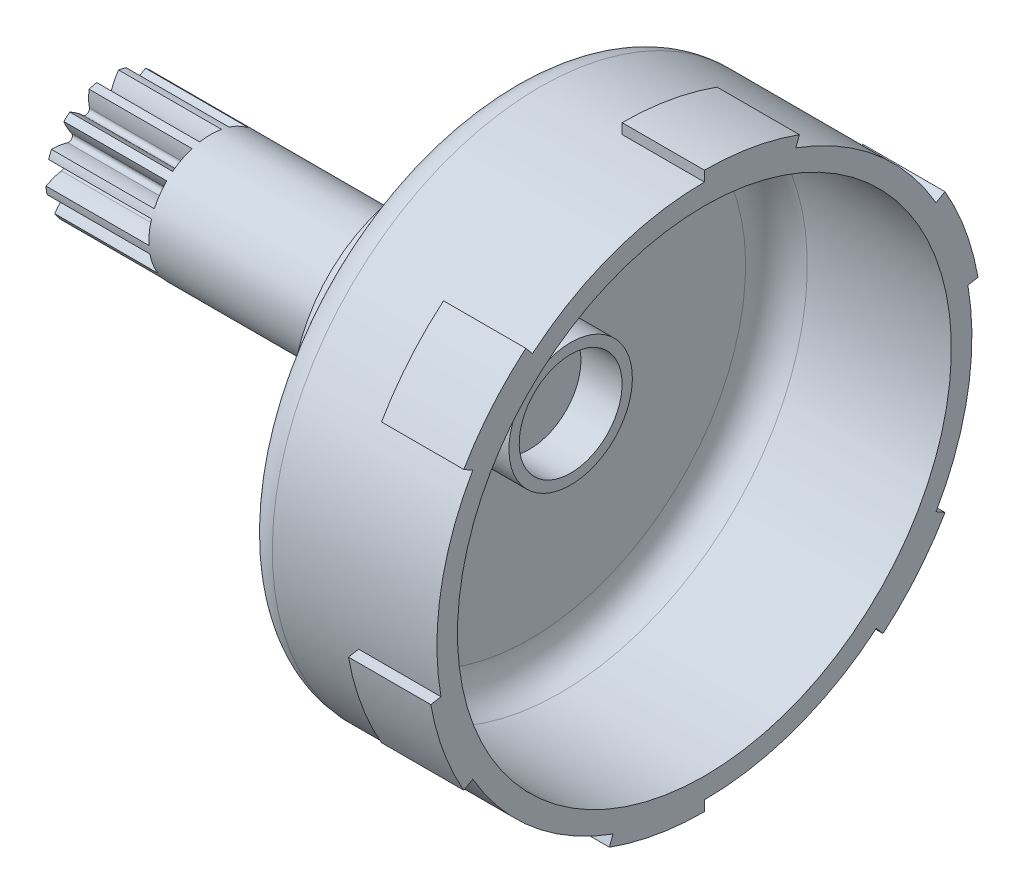
SolidWorks part; units mm, degrees
ref_plane "Front Plane" through (0, 0, 0) normal (0, 0, 1) x (1, 0, 0)
ref_plane "Top Plane" through (0, 0, 0) normal (0, 1, 0) x (1, 0, 0)
ref_plane "Right Plane" through (0, 0, 0) normal (1, 0, 0) x (0, 0, -1)
sketch "Sketch1" plane through (0, 0, 0) normal (0, 0, 1) x (1, 0, 0)
  line L0 (-19, 0) -> (-17, 0)
  line L1 (0, 0) -> (-19, 0) construction
  line L2 (0, 24) -> (0, 26)
  line L3 (0, 26) -> (-16, 26)
  line L4 (-19, 0) -> (-19, 23)
  line L7 (0, 24) -> (-14, 24)
  line L8 (-17, 0) -> (-17, 21)
  arc A0 (-14, 24) -> (-17, 21) centre (-14, 21) ccw
  arc A1 (-16, 26) -> (-19, 23) centre (-16, 23) ccw
  point P12 (-19, 26)
  dimension "D6" = 3
  dimension "D1" = 26
  dimension "D2" = 24
  dimension "D3" = 2
  dimension "D4" = 19
  dimension "D5" = 19
revolve "Revolve1" add sketch "Sketch1" angle 360 about L1
sketch "Sketch2" plane through (-17, 0, 0) normal (1, 0, 0) x (0, 0, -1)
  circle A0 centre (0, 0) radius 6
  circle A1 centre (0, 0) radius 5
  dimension "D1" = 12
  dimension "D2" = 10
extrude "Boss-Extrude1" add sketch "Sketch2" along normal blind 4
sketch "Sketch3" plane through (-19, 0, 0) normal (-1, 0, 0) x (0, 0, 1)
  circle A0 centre (0, 0) radius 12
  dimension "D1" = 24
extrude "Boss-Extrude2" add sketch "Sketch3" along normal blind 9
sketch "Sketch4" plane through (-28, 0, 0) normal (-1, 0, 0) x (0, 0, 1)
  circle A0 centre (0, 0) radius 6
  dimension "D1" = 12
extrude "Boss-Extrude3" add sketch "Sketch4" along normal blind 30
sketch "Sketch5" plane through (0, 0, 0) normal (1, 0, 0) x (0, 0, -1)
  line L0 (0, 26) -> (0, -26) construction
  line L1 (0, 26) -> (0, 27)
  line L2 (8.8925, 24.432) -> (9.2345, 25.3717)
  line L3 (22.5167, 13) -> (23.3827, 13.5)
  line L4 (25.605, 4.5149) -> (26.5898, 4.6885)
  line L5 (22.5167, -13) -> (23.3827, -13.5)
  line L6 (16.7125, -19.9172) -> (17.3553, -20.6832)
  line L7 (0, -26) -> (0, -27)
  line L8 (-8.8925, -24.432) -> (-9.2345, -25.3717)
  line L9 (-22.5167, -13) -> (-23.3827, -13.5)
  line L10 (-25.605, -4.5149) -> (-26.5898, -4.6885)
  line L11 (-22.5167, 13) -> (-23.3827, 13.5)
  line L12 (-16.7125, 19.9172) -> (-17.3553, 20.6832)
  circle A0 centre (0, 0) radius 26 construction
  arc A1 (9.2345, 25.3717) -> (0, 27) centre (0, 0) ccw
  arc A2 (0, 26) -> (8.8925, 24.432) centre (0, 0) cw
  arc A3 (26.5898, 4.6885) -> (23.3827, 13.5) centre (0, 0) ccw
  arc A4 (22.5167, 13) -> (25.605, 4.5149) centre (0, 0) cw
  arc A5 (17.3553, -20.6832) -> (23.3827, -13.5) centre (0, 0) ccw
  arc A6 (22.5167, -13) -> (16.7125, -19.9172) centre (0, 0) cw
  arc A7 (-9.2345, -25.3717) -> (0, -27) centre (0, 0) ccw
  arc A8 (0, -26) -> (-8.8925, -24.432) centre (0, 0) cw
  arc A9 (-26.5898, -4.6885) -> (-23.3827, -13.5) centre (0, 0) ccw
  arc A10 (-22.5167, -13) -> (-25.605, -4.5149) centre (0, 0) cw
  arc A11 (-17.3553, 20.6832) -> (-23.3827, 13.5) centre (0, 0) ccw
  arc A12 (-22.5167, 13) -> (-16.7125, 19.9172) centre (0, 0) cw
  point P34 (0, 0)
  dimension "D1" = 54
  dimension "D2" = 20
  dimension "D3" = 1
  dimension "D5" = 6
extrude "Boss-Extrude4" add sketch "Sketch5" against normal blind 8
sketch "Sketch6" plane through (-58, 0, 0) normal (-1, 0, 0) x (0, 0, 1)
  line L0 (0, 0) -> (0, 6) construction
  arc A0 (-1.06, 5.9056) -> (-0.35, 4.4864) centre (-5.5724, 2.761) cw
  arc A1 (-0.35, 4.4864) -> (0.35, 4.4864) centre (0, 4.602) ccw
  arc A2 (0.35, 4.4864) -> (1.06, 5.9056) centre (5.5724, 2.761) cw
  circle A3 centre (0, 0) radius 6 construction
  circle A4 centre (0, 0) radius 6
  circle A5 centre (0, 0) radius 4.5 construction
  arc A6 (1.8059, 5.7218) -> (1.775, 4.1351) centre (-3.651, 5.0344) cw
  arc A7 (2.3948, 3.8098) -> (3.6831, 4.7366) centre (6.2172, -0.1448) cw
  arc A8 (4.2581, 4.2271) -> (3.4934, 2.8366) centre (-0.8932, 6.1544) cw
  arc A9 (3.891, 2.2605) -> (5.4624, 2.4824) centre (5.4378, -3.0175) cw
  arc A10 (5.7348, 1.7641) -> (4.4115, 0.8882) centre (2.0692, 5.8646) cw
  arc A11 (4.4958, 0.1933) -> (5.9903, -0.3404) centre (3.4126, -5.1989) cw
  arc A12 (5.8977, -1.103) -> (4.3189, -1.2636) centre (4.5576, 4.2312) cw
  arc A13 (4.0707, -1.9181) -> (5.146, -3.0853) centre (0.6056, -6.1893) cw
  arc A14 (4.7096, -3.7175) -> (3.237, -3.126) centre (6.0019, 1.6285) cw
  arc A15 (2.713, -3.5902) -> (3.1227, -5.1233) centre (-2.3401, -5.7618) cw
  arc A16 (2.4425, -5.4803) -> (1.4135, -4.2722) centre (6.0712, -1.3472) cw
  arc A17 (0.7338, -4.4398) -> (0.3841, -5.9877) centre (-4.7497, -4.0144) cw
  arc A18 (-0.3841, -5.9877) -> (-0.7338, -4.4398) centre (4.7497, -4.0144) cw
  arc A19 (-1.4135, -4.2722) -> (-2.4425, -5.4803) centre (-6.0712, -1.3472) cw
  arc A20 (-3.1227, -5.1233) -> (-2.713, -3.5902) centre (2.3401, -5.7618) cw
  arc A21 (-3.237, -3.126) -> (-4.7096, -3.7175) centre (-6.0019, 1.6285) cw
  arc A22 (-5.146, -3.0853) -> (-4.0707, -1.9181) centre (-0.6056, -6.1893) cw
  arc A23 (-4.3189, -1.2636) -> (-5.8977, -1.103) centre (-4.5576, 4.2312) cw
  arc A24 (-5.9903, -0.3404) -> (-4.4958, 0.1933) centre (-3.4126, -5.1989) cw
  arc A25 (-4.4115, 0.8882) -> (-5.7348, 1.7641) centre (-2.0692, 5.8646) cw
  arc A26 (-5.4624, 2.4824) -> (-3.891, 2.2605) centre (-5.4378, -3.0175) cw
  arc A27 (-3.4934, 2.8366) -> (-4.2581, 4.2271) centre (0.8932, 6.1544) cw
  arc A28 (-3.6831, 4.7366) -> (-2.3948, 3.8098) centre (-6.2172, -0.1448) cw
  arc A29 (-1.775, 4.1351) -> (-1.8059, 5.7218) centre (3.651, 5.0344) cw
  arc A30 (-2.3948, 3.8098) -> (-1.775, 4.1351) centre (-2.1387, 4.0749) ccw
  arc A31 (1.775, 4.1351) -> (2.3948, 3.8098) centre (2.1387, 4.0749) ccw
  arc A32 (3.4934, 2.8366) -> (3.891, 2.2605) centre (3.7874, 2.6142) ccw
  arc A33 (4.4115, 0.8882) -> (4.4958, 0.1933) centre (4.5684, 0.5547) ccw
  arc A34 (4.3189, -1.2636) -> (4.0707, -1.9181) centre (4.3029, -1.6319) ccw
  arc A35 (3.237, -3.126) -> (2.713, -3.5902) centre (3.0517, -3.4446) ccw
  arc A36 (1.4135, -4.2722) -> (0.7338, -4.4398) centre (1.1013, -4.4683) ccw
  arc A37 (-0.7338, -4.4398) -> (-1.4135, -4.2722) centre (-1.1013, -4.4683) ccw
  arc A38 (-2.713, -3.5902) -> (-3.237, -3.126) centre (-3.0517, -3.4446) ccw
  arc A39 (-4.0707, -1.9181) -> (-4.3189, -1.2636) centre (-4.3029, -1.6319) ccw
  arc A40 (-4.4958, 0.1933) -> (-4.4115, 0.8882) centre (-4.5684, 0.5547) ccw
  arc A41 (-3.891, 2.2605) -> (-3.4934, 2.8366) centre (-3.7874, 2.6142) ccw
  point P88 (0, 0)
  point P126 (0, 0)
  circle M1 centre (0, 0) radius 6
  dimension "D2" = 1.06
  dimension "D3" = 5.5
  dimension "D4" = 9
  dimension "D5" = 5.5
  dimension "D9" = 13
  dimension "D1" = 2.12
  dimension "D6" = 0.35
  dimension "D7" = 0.35
  dimension "D8" = 13
extrude "Cut-Extrude2" cut sketch "Sketch6" against normal blind 10 contours A28 A30 A29 A4 | A26 A41 A27 A4 | A24 A40 A25 A4 | A22 A39 A23 A4 | A20 A38 A21 A4 | A18 A37 A19 A4 | A16 A36 A17 A4 | A14 A35 A15 A4 | A12 A34 A13 A4 | A10 A33 A11 A4 | A8 A32 A9 A4 | A6 A31 A7 A4 | A1 A2 A0 M1
